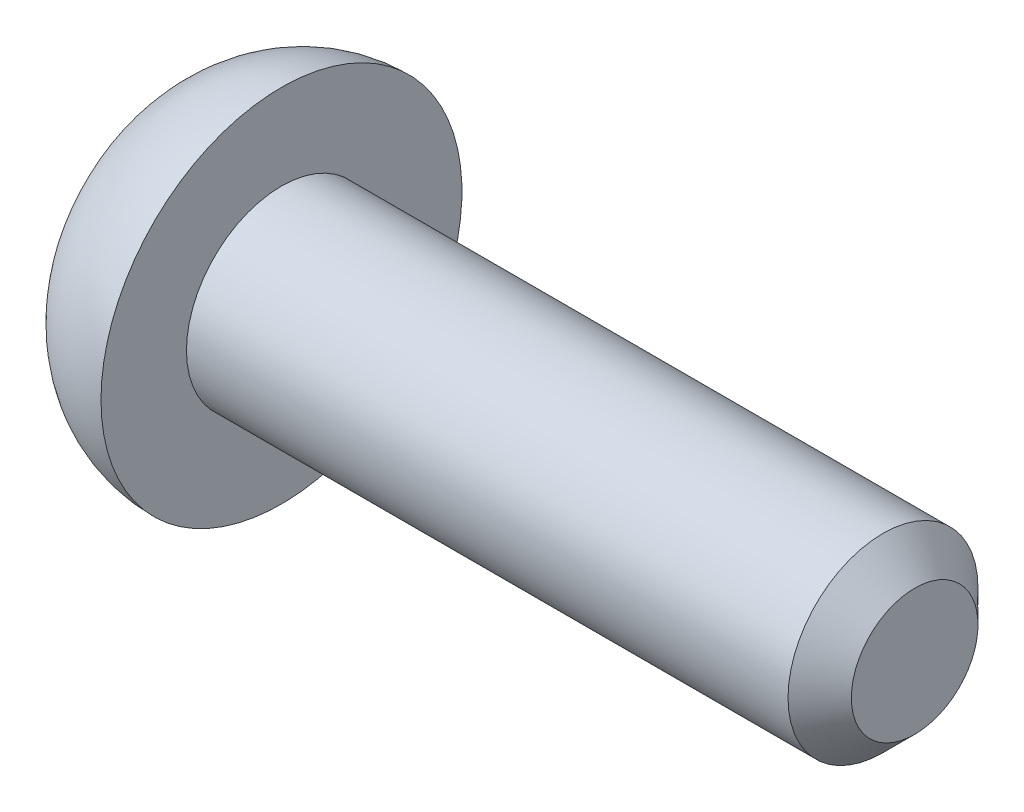
SolidWorks part; units mm, degrees
ref_plane "Front Plane" through (0, 0, 0) normal (0, 0, 1) x (1, 0, 0)
ref_plane "Top Plane" through (0, 0, 0) normal (0, 1, 0) x (1, 0, 0)
ref_plane "Right Plane" through (0, 0, 0) normal (1, 0, 0) x (0, 0, -1)
sketch "Sketch2" plane through (0, 0, 0) normal (0, 1, 0) x (1, 0, 0)
  line L0 (0, 0) -> (0, 1.5)
  line L1 (0, -55) -> (0, 55) construction
  line L2 (0, 1.5) -> (-10, 1.5)
  line L3 (-10, 1.5) -> (-10, 0) construction
  line L4 (-55, 0) -> (55, 0) construction
  line L5 (-11.65, 2.049) -> (-11.65, 0)
  line L6 (-11.65, 0) -> (0, 0)
  line L7 (-10, 2.85) -> (-10, 1.5)
  arc A0 (-11.65, 2.049) -> (-10, 2.85) centre (-10, 0.75) cw
  dimension "D2" = 10
  dimension "D3" = 2.85
  dimension "D1" = 1.65
  dimension "D4" = 1.5
revolve "Revolve1" add sketch "Sketch2" angle 360 about L6
chamfer "Chamfer1" distance 0.5 angle 45 1 edges at (0, 0, 1.5)
sketch "Sketch4" plane through (-11.65, 0, 0) normal (-1, 0, 0) x (0, 0, 1)
  line L1 (0.8389, 1.453) -> (-0.8389, 1.453) construction
  line L2 (-0.8389, 1.453) -> (-1.6778, 0) construction
  line L3 (-1.6778, 0) -> (-0.8389, -1.453) construction
  line L4 (-0.8389, -1.453) -> (0.8389, -1.453) construction
  line L5 (0.8389, -1.453) -> (1.6778, 0) construction
  line L6 (1.6778, 0) -> (0.8389, 1.453) construction
  circle A0 centre (0, 0) radius 1.453 construction
  arc A1 (-1.342, 0.0907) -> (-0.7496, 1.1169) centre (-1.7745, 1.0245) ccw
  arc A2 (-0.5924, 1.2076) -> (0.5924, 1.2076) centre (0, 2.049) ccw
  arc A3 (0.7496, 1.1169) -> (1.342, 0.0907) centre (1.7745, 1.0245) ccw
  arc A4 (1.342, -0.0907) -> (0.7496, -1.1169) centre (1.7745, -1.0245) ccw
  arc A5 (-0.5924, -1.2076) -> (0.5924, -1.2076) centre (0, -2.049) cw
  arc A6 (-0.7496, -1.1169) -> (-1.342, -0.0907) centre (-1.7745, -1.0245) ccw
  circle A7 centre (0, 0) radius 2.049 construction
  arc A8 (0.7496, 1.1169) -> (0.5924, 1.2076) centre (0.65, 1.1258) ccw
  arc A9 (1.342, -0.0907) -> (1.342, 0.0907) centre (1.3, 0) ccw
  arc A10 (0.7496, -1.1169) -> (0.5924, -1.2076) centre (0.65, -1.1258) cw
  arc A11 (-0.7496, -1.1169) -> (-0.5924, -1.2076) centre (-0.65, -1.1258) ccw
  arc A12 (-1.342, 0.0907) -> (-1.342, -0.0907) centre (-1.3, 0) ccw
  arc A13 (-0.7496, 1.1169) -> (-0.5924, 1.2076) centre (-0.65, 1.1258) cw
  circle A14 centre (0, 0) radius 2.049 construction
  point P40 (2.049, 0)
  dimension "D1" = 0.1
  dimension "D2" = 2.6
extrude "Cut-Extrude1" cut sketch "Sketch4" against normal blind 1
equation "\"d1\"= 3"
equation "\"l\"= 10"
equation "\"d2\"= 5.7"
equation "\"t\"= 1"
equation "\"k\"=1.65"
equation "\"A\"=2.8"
equation "\"D3@Sketch2\"=\"d2\" / 2"
equation "\"D1@Sketch2\"= \"k\""
equation "\"D4@Sketch2\"=\"d1\" / 2"
equation "\"D2@Sketch4\"= \"A\" - 2 * \"D1@Sketch4\""
equation "\"D1@Cut-Extrude1\"= \"t\""
